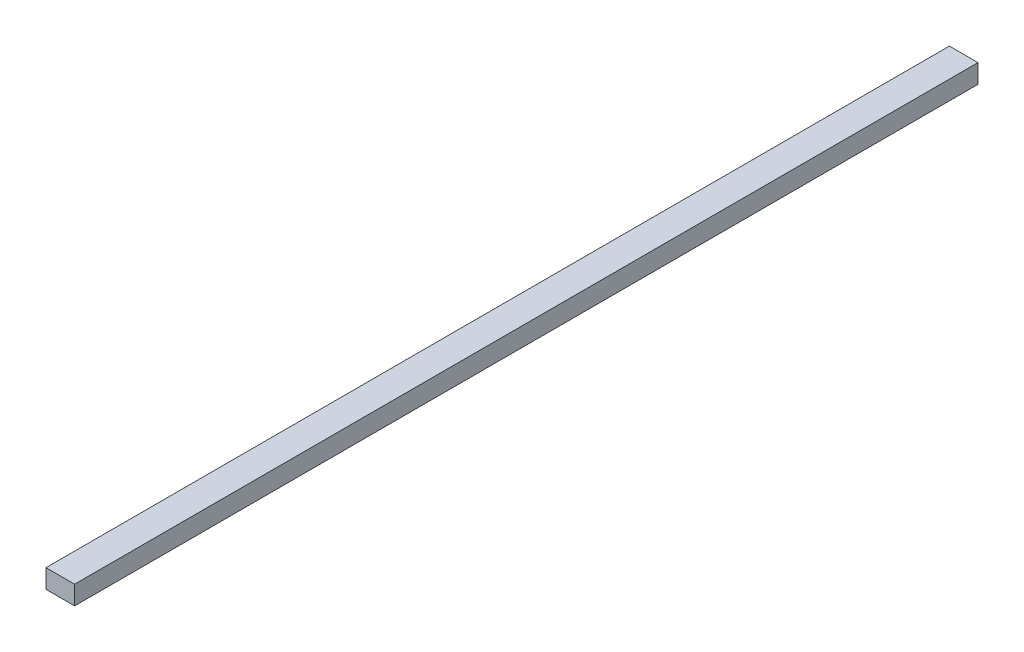
SolidWorks part; units mm, degrees
ref_plane "Front Plane" through (0, 0, 0) normal (0, 0, 1) x (1, 0, 0)
ref_plane "Top Plane" through (0, 0, 0) normal (0, 1, 0) x (1, 0, 0)
ref_plane "Right Plane" through (0, 0, 0) normal (1, 0, 0) x (0, 0, -1)
sketch "Sketch1" plane through (0, 0, 0) normal (0, 0, 1) x (1, 0, 0)
  line L1 (4.826, -3.175) -> (-4.826, -3.175)
  line L2 (4.826, -3.175) -> (4.826, 3.175)
  line L3 (4.826, 3.175) -> (-4.826, 3.175)
  line L4 (-4.826, -3.175) -> (-4.826, 3.175)
  line L5 (4.826, -3.175) -> (-4.826, 3.175) construction
  line L6 (4.826, 3.175) -> (-4.826, -3.175) construction
  point P0 (0, 0)
  dimension "D1" = 6.35
  dimension "D2" = 9.652
extrude "Boss-Extrude1" add sketch "Sketch1" along normal blind 304.8
